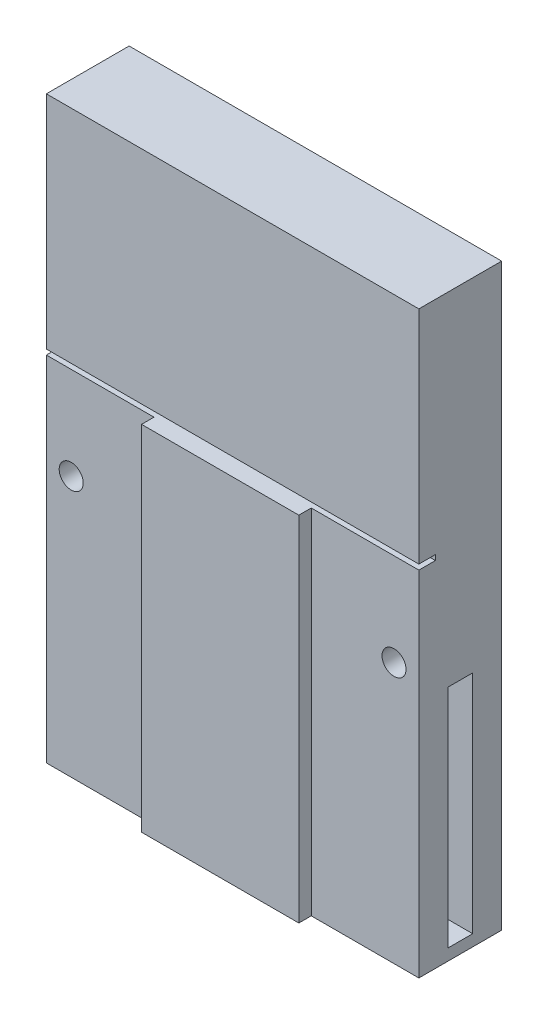
SolidWorks part; units mm, degrees
ref_plane "Front Plane" through (0, 0, 0) normal (0, 0, 1) x (1, 0, 0)
ref_plane "Top Plane" through (0, 0, 0) normal (0, 1, 0) x (1, 0, 0)
ref_plane "Right Plane" through (0, 0, 0) normal (1, 0, 0) x (0, 0, -1)
sketch "Sketch2" plane through (0, 0, 0) normal (0, 1, 0) x (1, 0, 0)
  line L1 (22.5, 5) -> (-22.5, 5)
  line L2 (22.5, 5) -> (22.5, -5)
  line L3 (22.5, -5) -> (-22.5, -5)
  line L4 (-22.5, 5) -> (-22.5, -5)
  line L5 (22.5, 5) -> (-22.5, -5) construction
  line L6 (22.5, -5) -> (-22.5, 5) construction
  point P0 (0, 0)
  dimension "D1" = 10
  dimension "D2" = 45
extrude "Boss-Extrude1" add sketch "Sketch2" along normal blind 40
sketch "Sketch3" plane through (0, 0, -5) normal (0, 0, -1) x (-1, 0, 0)
  line L0 (0, 0) -> (0, 40) construction
  line L1 (-22.5, 40) -> (22.5, 40) construction
  line L3 (22.5, 40) -> (22.5, 0) construction
  line L4 (-22.5, 40) -> (-22.5, 0) construction
  line L5 (-22.5, 0) -> (22.5, 0) construction
  line L6 (-22.5, 11.5) -> (22.5, 11.5) construction
  circle A0 centre (19.5, 2.25) radius 1.45
  circle A3 centre (-19.5, 2.25) radius 1.45
  circle A4 centre (-19.5, 20.75) radius 1.45
  circle A5 centre (19.5, 20.75) radius 1.45
  dimension "D3" = 2.9
  dimension "D4" = 3
  dimension "D1" = 3
  dimension "D2" = 2.25
sketch "Sketch4" plane through (0, 40, 0) normal (0, 1, 0) x (1, 0, 0)
  line L1 (-22.5, 5) -> (22.5, 5)
  line L2 (-22.5, 5) -> (-22.5, -5)
  line L3 (-22.5, -5) -> (22.5, -5)
  line L4 (22.5, 5) -> (22.5, -5)
extrude "Boss-Extrude2" add sketch "Sketch4" along normal blind 10
sketch "Sketch6" plane through (0, 0, -5) normal (0, 0, -1) x (-1, 0, 0)
  line L2 (-22.5, 23) -> (22.7712, 23) construction
  circle A1 centre (-19.5, 20.75) radius 1.45 construction
  dimension "D1" = 2.25
sketch "Sketch8" plane through (0, 0, 0) normal (0, -1, 0) x (1, 0, 0)
  line L1 (-22.5, 5) -> (22.5, 5)
  line L2 (-22.5, 5) -> (-22.5, -5)
  line L3 (-22.5, -5) -> (22.5, -5)
  line L4 (22.5, 5) -> (22.5, -5)
extrude "Boss-Extrude3" add sketch "Sketch8" along normal blind 20
sketch "Sketch9" plane through (0, 0, 5) normal (0, 0, 1) x (1, 0, 0)
  line L0 (22.5, 11.5) -> (-22.5, 11.5) construction
  line L1 (-22.5, 50) -> (-22.5, -20) construction
  line L2 (22.5, 50) -> (22.5, -20) construction
  circle A0 centre (19.5, 20.75) radius 1.45 construction
  circle A1 centre (19.5, 2.25) radius 1.45 construction
  circle A2 centre (19.5, 11.5) radius 1.45
  circle A3 centre (-19.5, 11.5) radius 1.45
  dimension "D1" = 18.5
  dimension "D2" = 3
  dimension "D3" = 3
  dimension "D4" = 3
extrude "Cut-Extrude2" cut sketch "Sketch9" against normal blind 20
sketch "Sketch10" plane through (0, 0, 5) normal (0, 0, 1) x (1, 0, 0)
  line L1 (-22.5, 50) -> (-22.5, -20) construction
  line L2 (-22.5, 23.2975) -> (22.5, 23.2975)
  line L3 (-22.5, 23.2975) -> (-22.5, 22.6713)
  line L4 (-22.5, 22.6713) -> (22.5, 22.6713)
  line L5 (22.5, 23.2975) -> (22.5, 22.6713)
  line L6 (22.5, 50) -> (22.5, -20) construction
extrude "Cut-Extrude3" cut sketch "Sketch10" against normal blind 2
sketch "Sketch11" plane through (0, 0, 5) normal (0, 0, 1) x (1, 0, 0)
  line L0 (-22.5, 22.6713) -> (22.5, 22.6713) construction
  line L1 (-9.5, 22.6713) -> (9.5, 22.6713)
  line L2 (-9.5, 22.6713) -> (-9.5, -20)
  line L3 (-9.5, -20) -> (9.5, -20)
  line L4 (9.5, 22.6713) -> (9.5, -20)
  line L5 (22.5, -20) -> (-22.5, -20) construction
  line L6 (22.5, 22.6713) -> (22.5, -20) construction
  line L8 (-22.5, 22.6713) -> (-22.5, -20) construction
  dimension "D1" = 19
  dimension "D2" = 13
  dimension "D3" = 13
extrude "Boss-Extrude4" add sketch "Sketch11" along normal blind 1.5
sketch "Sketch12" plane through (22.5, 0, 0) normal (1, 0, 0) x (0, 0, -1)
  line L0 (0, 8.6713) -> (0, -20) construction
  line L1 (5, -20) -> (-5, -20) construction
  line L2 (-3, 22.6713) -> (-5, 22.6713) construction
  line L3 (-1.5, 8.6713) -> (1.5, 8.6713)
  line L4 (-1.5, 8.6713) -> (-1.5, -18.615)
  line L5 (-1.5, -18.615) -> (1.5, -18.615)
  line L6 (1.5, 8.6713) -> (1.5, -18.615)
  point P8 (0, 0)
  point P9 (0, 0)
  dimension "D1" = 3
  dimension "D2" = 1.385
  dimension "D3" = 14
extrude "Cut-Extrude6" cut sketch "Sketch12" against normal blind 10
